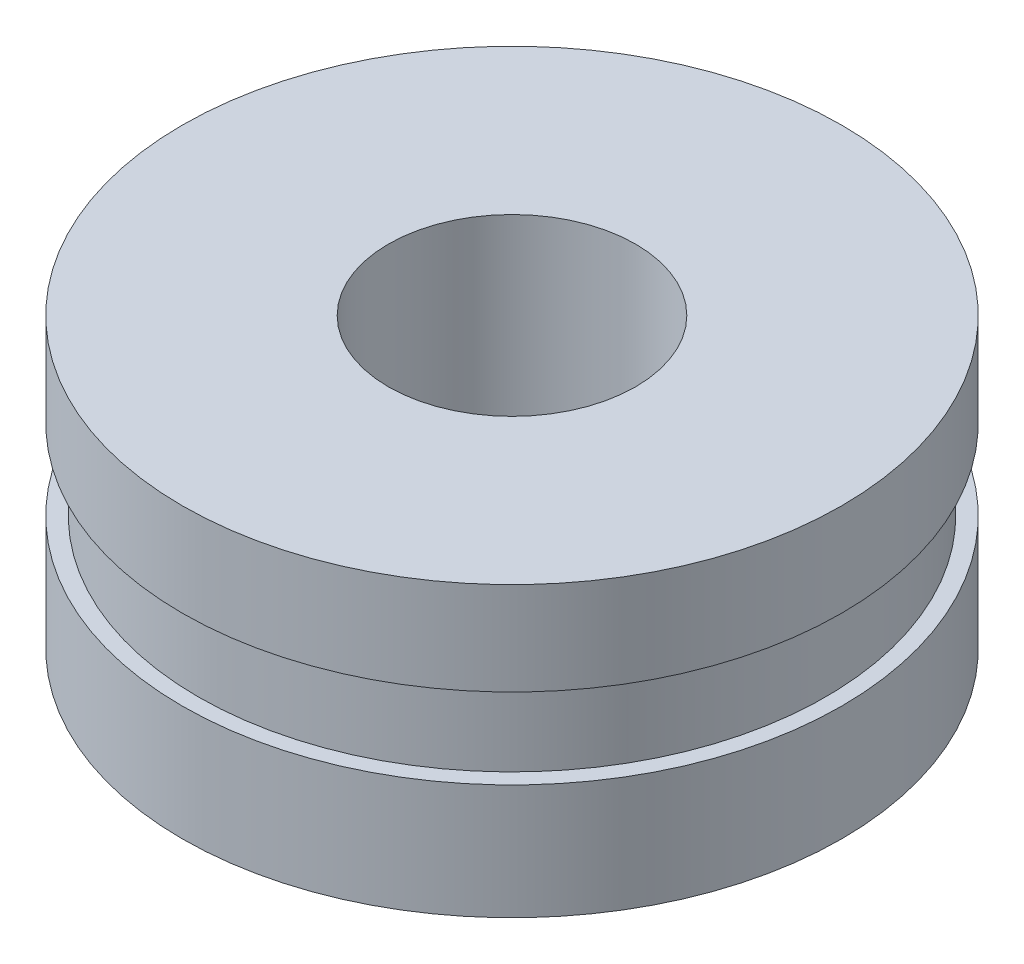
SolidWorks part; units mm, degrees
ref_plane "前视基准面" through (0, 0, 0) normal (0, 0, 1) x (1, 0, 0)
ref_plane "上视基准面" through (0, 0, 0) normal (0, 1, 0) x (1, 0, 0)
ref_plane "右视基准面" through (0, 0, 0) normal (1, 0, 0) x (0, 0, -1)
sketch "草图1" plane through (0, 0, 0) normal (0, 1, 0) x (1, 0, 0)
  circle A0 centre (0, 0) radius 1.5
  circle A1 centre (0, 0) radius 4
  dimension "D1" = 3
  dimension "D2" = 8
extrude "凸台-拉伸1" add sketch "草图1" along normal blind 3.5
sketch "草图2" plane through (0, 0, 0) normal (0, 0, 1) x (1, 0, 0)
  line L0 (-4, 2.3713) -> (-3.8068, 2.3713)
  line L1 (-4, 3.5) -> (-4, 0) construction
  line L2 (-3.8068, 2.3713) -> (-3.8068, 1.3954)
  line L3 (-3.8068, 1.3954) -> (-4, 1.3954)
  line L4 (-4, 1.3954) -> (-4, 2.3713)
ref_axis "基准轴1" through (0, 3.5, 0) along (0, -1, 0)
revolve "切除-旋转1" cut sketch "草图2" angle 360 about axis through (0, 3.5, 0) along (0, -1, 0)
